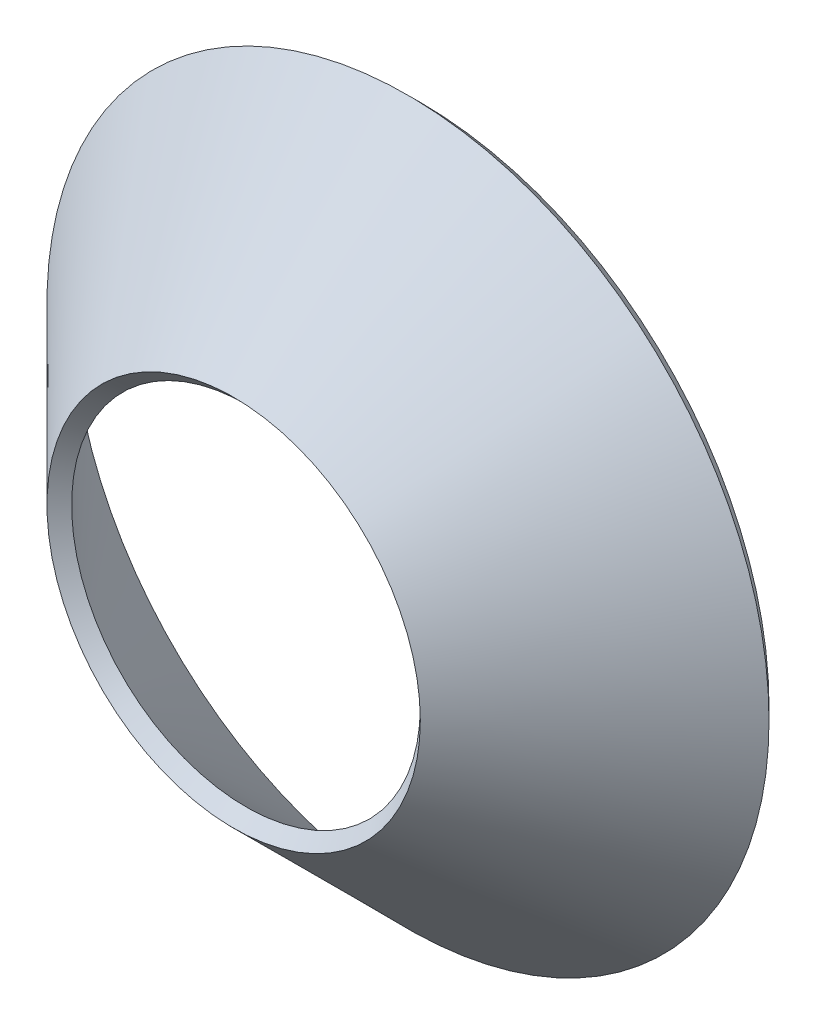
SolidWorks part; units mm, degrees
ref_plane "Front Plane" through (0, 0, 0) normal (1, 0, 0) x (0, 1, 0)
ref_plane "Top Plane" through (0, 0, 0) normal (0, 0, 1) x (0, 1, 0)
ref_plane "Right Plane" through (0, 0, 0) normal (0, 1, 0) x (-1, 0, 0)
sketch "Sketch1" plane through (0, 0, 0) normal (1, 0, 0) x (0, 1, 0)
  line L0 (25.4, 25.4) -> (50.8, 0)
  line L1 (13.8471, 0) -> (-13.8471, 0) construction
  line L2 (0, -13.8471) -> (0, 13.8471) construction
  dimension "D1" = 45
  dimension "D2" = 25.4
  dimension "D3" = 25.4
ref_axis "Axis1" through (0, 0, 26.67) along (0, 0, -1)
revolve "Revolve-Thin1" add sketch "Sketch1" angle 360 about axis through (0, 0, 26.67) along (0, 0, -1) wall 2.54
